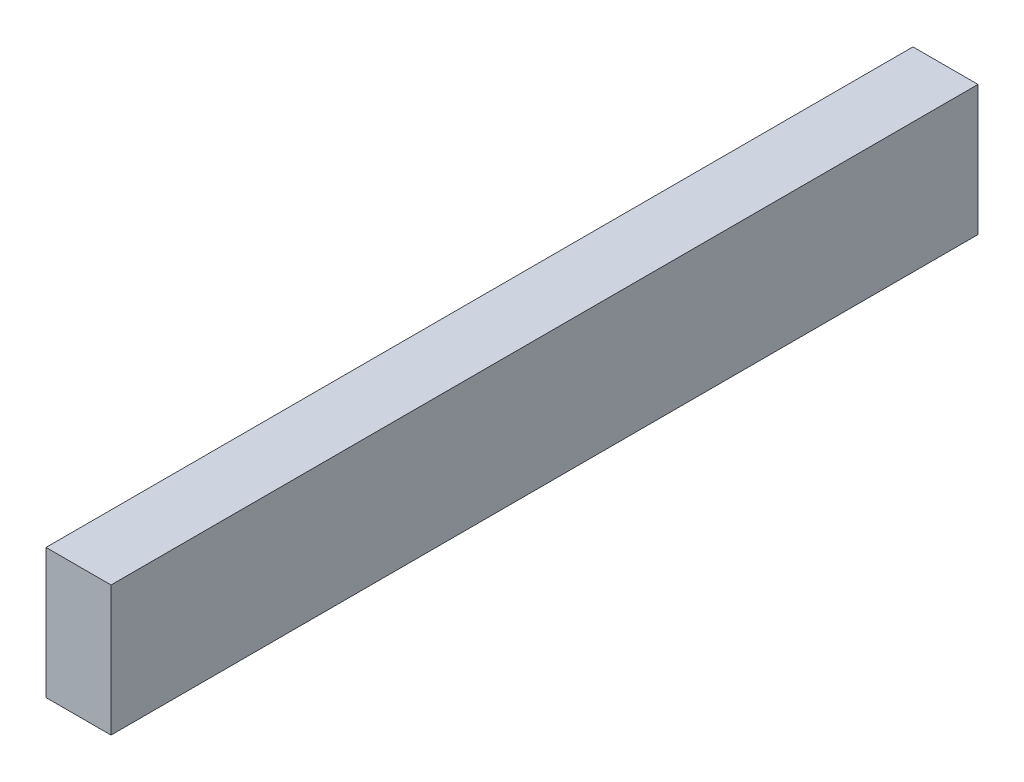
SolidWorks part; units mm, degrees
ref_plane "Front Plane" through (0, 0, 0) normal (0, 0, 1) x (1, 0, 0)
ref_plane "Top Plane" through (0, 0, 0) normal (0, 1, 0) x (1, 0, 0)
ref_plane "Right Plane" through (0, 0, 0) normal (1, 0, 0) x (0, 0, -1)
sketch "Sketch1" plane through (0, 0, 0) normal (0, 0, 1) x (1, 0, 0)
  line L1 (-15, -30) -> (15, -30)
  line L2 (-15, -30) -> (-15, 30)
  line L3 (-15, 30) -> (15, 30)
  line L4 (15, -30) -> (15, 30)
  line L5 (-15, -30) -> (15, 30) construction
  line L6 (-15, 30) -> (15, -30) construction
  point P0 (0, 0)
  dimension "D1" = 60
  dimension "D2" = 30
extrude "Boss-Extrude1" add sketch "Sketch1" along normal mid plane 400
